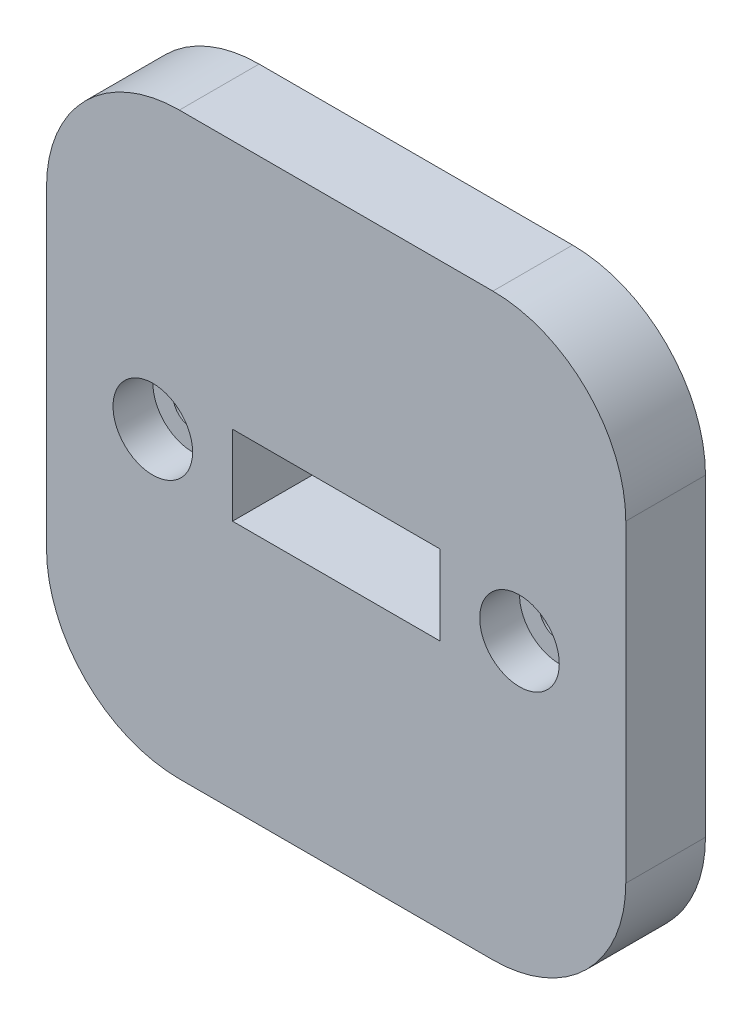
SolidWorks part; units mm, degrees
ref_plane "Plan de face" through (0, 0, 0) normal (0, 0, 1) x (1, 0, 0)
ref_plane "Plan de dessus" through (0, 0, 0) normal (0, 1, 0) x (1, 0, 0)
ref_plane "Plan de droite" through (0, 0, 0) normal (1, 0, 0) x (0, 0, -1)
sketch "Esquisse1" plane through (0, 0, 0) normal (0, 0, 1) x (1, 0, 0)
  line L1 (0, 0) -> (43.6, 0)
  line L2 (0, 0) -> (0, 43.6)
  line L3 (0, 43.6) -> (43.6, 43.6)
  line L4 (43.6, 0) -> (43.6, 43.6)
  dimension "D1" = 43.6
  dimension "D2" = 43.6
extrude "Boss.-Extru.1" add sketch "Esquisse1" along normal blind 6
fillet "Congé1" radius 10 4 edges at (43.6, 0, 3) (0, 0, 3) (43.6, 43.6, 3) (0, 43.6, 3)
sketch "Esquisse2" plane through (0, 0, 6) normal (0, 0, 1) x (1, 0, 0)
  line L0 (10, 0) -> (33.6, 0) construction
  line L1 (14, 18.8) -> (29.6, 18.8)
  line L2 (14, 18.8) -> (14, 24.8)
  line L3 (14, 24.8) -> (29.6, 24.8)
  line L4 (29.6, 18.8) -> (29.6, 24.8)
  line L5 (33.6, 43.6) -> (10, 43.6) construction
  line L6 (43.6, 10) -> (43.6, 33.6) construction
  line L7 (0, 33.6) -> (0, 10) construction
  circle A0 centre (8, 21.8) radius 1.5
  circle A1 centre (35.6, 21.8) radius 1.5
  dimension "D6" = 21.8
  dimension "D7" = 21.8
  dimension "D8" = 3
  dimension "D9" = 3
  dimension "D10" = 6
  dimension "D11" = 6
  dimension "D1" = 6
  dimension "D2" = 18.8
  dimension "D3" = 18.8
  dimension "D4" = 14
  dimension "D5" = 14
extrude "Enlèv. mat.-Extru.1" cut sketch "Esquisse2" against normal blind 6
sketch "Esquisse3" plane through (0, 0, 6) normal (0, 0, 1) x (1, 0, 0)
  circle A0 centre (8, 21.8) radius 2.995
  circle A1 centre (35.6, 21.8) radius 2.995
  dimension "D1" = 5.99
  dimension "D2" = 5.99
extrude "Enlèv. mat.-Extru.2" cut sketch "Esquisse3" against normal blind 3
